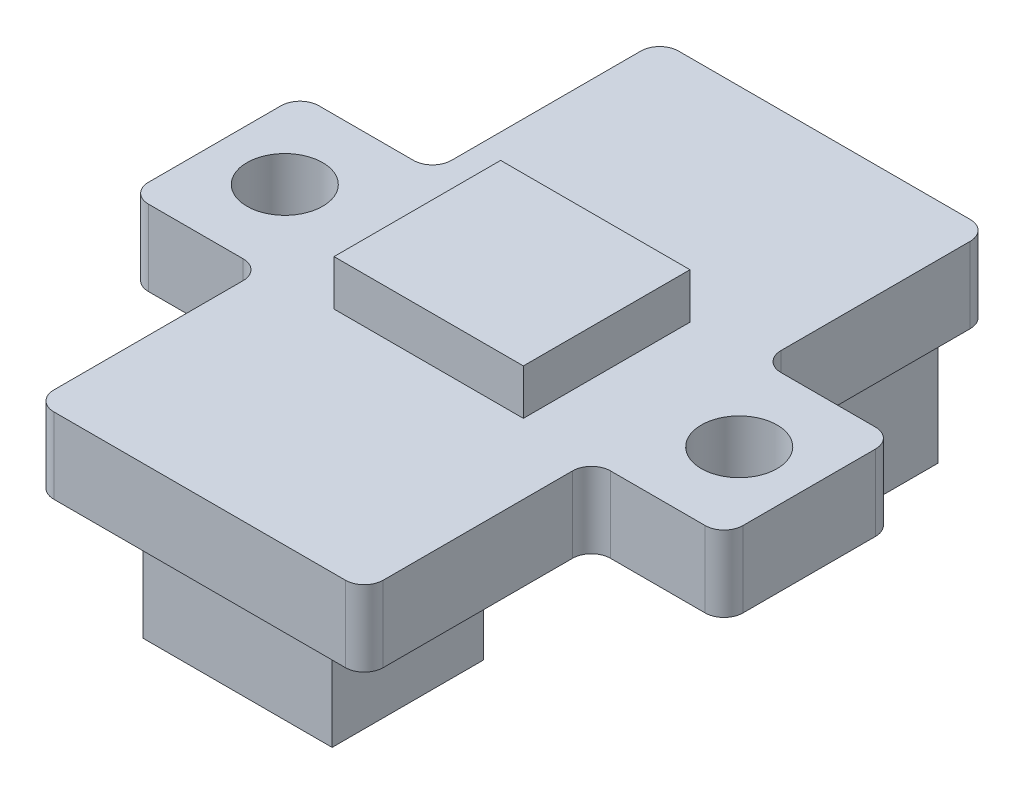
SolidWorks part; units mm, degrees
ref_plane "Front Plane" through (0, 0, 0) normal (0, 0, 1) x (1, 0, 0)
ref_plane "Top Plane" through (0, 0, 0) normal (0, 1, 0) x (1, 0, 0)
ref_plane "Right Plane" through (0, 0, 0) normal (1, 0, 0) x (0, 0, -1)
sketch "Sketch1" plane through (0, 0, 0) normal (0, 1, 0) x (1, 0, 0)
  line L0 (0, 0) -> (0, 8.25) construction
  line L1 (-7.85, 8.25) -> (7.85, 8.25) construction
  line L2 (-7.85, 8.25) -> (-7.85, -8.25) construction
  line L3 (-7.85, -8.25) -> (7.85, -8.25) construction
  line L4 (7.85, 8.25) -> (7.85, -8.25) construction
  line L5 (-7.85, 8.25) -> (7.85, -8.25) construction
  line L6 (-7.85, -8.25) -> (7.85, 8.25) construction
  line L7 (-4.35, 8.25) -> (4.35, 8.25)
  line L8 (-4.35, 8.25) -> (-4.35, -8.25)
  line L9 (-4.35, -8.25) -> (4.35, -8.25)
  line L10 (4.35, 8.25) -> (4.35, -8.25)
  line L11 (0, 0) -> (7.85, 0) construction
  line L13 (-7.85, 2.25) -> (7.85, 2.25)
  line L14 (-7.85, 2.25) -> (-7.85, -2.25)
  line L15 (-7.85, -2.25) -> (7.85, -2.25)
  line L16 (7.85, 2.25) -> (7.85, -2.25)
  circle A0 centre (6, 0) radius 1
  circle A1 centre (-6, 0) radius 1
  point P0 (0, 0)
  dimension "D5" = 2
  dimension "D1" = 15.7
  dimension "D2" = 16.5
  dimension "D3" = 8.7
  dimension "D4" = 12
  dimension "D6" = 4.5
extrude "Boss-Extrude1" add sketch "Sketch1" along normal blind 2 contours L8 L13 L10 L7 | L8 L15 L10 L13 | L14 L15 L8 L13 A1 | L16 L13 L10 L15 A0 | L15 L8 L9 L10
fillet "Fillet1" radius 0.5 12 edges at (-7.85, 1, -2.25) (-4.35, 1, -2.25) (-4.35, 1, -8.25) (4.35, 1, -8.25) (4.35, 1, -2.25) (7.85, 1, -2.25) (7.85, 1, 2.25) (4.35, 1, 2.25) (4.35, 1, 8.25) (-4.35, 1, 8.25) (-7.85, 1, 2.25) (-4.35, 1, 2.25)
sketch "Sketch2" plane through (0, 0, 0) normal (0, -1, 0) x (1, 0, 0)
  line L0 (0, 8.25) -> (0, -8.25) construction
  line L1 (-2.5, 7.25) -> (2.5, 7.25)
  line L2 (-2.5, 7.25) -> (-2.5, 3.25)
  line L3 (-2.5, 3.25) -> (2.5, 3.25)
  line L4 (2.5, 7.25) -> (2.5, 3.25)
  line L5 (-3.85, -8.25) -> (3.85, -8.25) construction
  line L6 (-4, -2.75) -> (4, -2.75)
  line L7 (-4, -2.75) -> (-4, -7.25)
  line L8 (-4, -7.25) -> (4, -7.25)
  line L9 (4, -2.75) -> (4, -7.25)
  line L12 (-7.35, -2.25) -> (-4.85, -2.25)
  line L13 (-3.85, -8.25) -> (3.85, -8.25)
  line L14 (-7.35, -2.25) -> (-4.85, -2.25)
  line L15 (-4.35, -2.75) -> (-4.35, -7.75)
  line L16 (7.85, -1.75) -> (7.85, 1.75)
  line L17 (-4.35, -2.75) -> (-4.35, -7.75)
  line L18 (4.35, -7.75) -> (4.35, -2.75)
  line L19 (3.85, 8.25) -> (-3.85, 8.25)
  line L20 (4.35, -7.75) -> (4.35, -2.75)
  line L21 (4.85, -2.25) -> (7.35, -2.25)
  line L22 (-7.85, 1.75) -> (-7.85, -1.75)
  line L23 (4.85, -2.25) -> (7.35, -2.25)
  line L25 (-3.85, -8.25) -> (3.85, -8.25) construction
  line L28 (7.85, -1.75) -> (7.85, 1.75) construction
  line L31 (3.85, 8.25) -> (-3.85, 8.25) construction
  line L34 (-7.85, 1.75) -> (-7.85, -1.75) construction
  line L46 (7.35, 2.25) -> (4.85, 2.25)
  line L47 (7.35, 2.25) -> (4.85, 2.25)
  line L48 (4.35, 2.75) -> (4.35, 7.75)
  line L49 (4.35, 2.75) -> (4.35, 7.75)
  line L50 (-4.35, 7.75) -> (-4.35, 2.75)
  line L51 (-4.35, 7.75) -> (-4.35, 2.75)
  line L52 (-4.85, 2.25) -> (-7.35, 2.25)
  line L53 (-4.85, 2.25) -> (-7.35, 2.25)
  arc A12 (-7.85, -1.75) -> (-7.35, -2.25) centre (-7.35, -1.75) ccw
  arc A13 (-7.85, -1.75) -> (-7.35, -2.25) centre (-7.35, -1.75) ccw
  arc A14 (-4.35, -2.75) -> (-4.85, -2.25) centre (-4.85, -2.75) ccw
  arc A15 (-4.35, -2.75) -> (-4.85, -2.25) centre (-4.85, -2.75) ccw
  arc A16 (-4.35, -7.75) -> (-3.85, -8.25) centre (-3.85, -7.75) ccw
  arc A17 (-4.35, -7.75) -> (-3.85, -8.25) centre (-3.85, -7.75) ccw
  arc A18 (3.85, -8.25) -> (4.35, -7.75) centre (3.85, -7.75) ccw
  arc A19 (3.85, -8.25) -> (4.35, -7.75) centre (3.85, -7.75) ccw
  arc A20 (4.85, -2.25) -> (4.35, -2.75) centre (4.85, -2.75) ccw
  arc A21 (4.85, -2.25) -> (4.35, -2.75) centre (4.85, -2.75) ccw
  arc A22 (7.35, -2.25) -> (7.85, -1.75) centre (7.35, -1.75) ccw
  arc A23 (7.35, -2.25) -> (7.85, -1.75) centre (7.35, -1.75) ccw
  arc A24 (7.85, 1.75) -> (7.35, 2.25) centre (7.35, 1.75) ccw
  arc A25 (7.85, 1.75) -> (7.35, 2.25) centre (7.35, 1.75) ccw
  arc A26 (4.35, 2.75) -> (4.85, 2.25) centre (4.85, 2.75) ccw
  arc A27 (4.35, 2.75) -> (4.85, 2.25) centre (4.85, 2.75) ccw
  arc A28 (4.35, 7.75) -> (3.85, 8.25) centre (3.85, 7.75) ccw
  arc A29 (4.35, 7.75) -> (3.85, 8.25) centre (3.85, 7.75) ccw
  arc A30 (-3.85, 8.25) -> (-4.35, 7.75) centre (-3.85, 7.75) ccw
  arc A31 (-3.85, 8.25) -> (-4.35, 7.75) centre (-3.85, 7.75) ccw
  arc A32 (-4.85, 2.25) -> (-4.35, 2.75) centre (-4.85, 2.75) ccw
  arc A33 (-4.85, 2.25) -> (-4.35, 2.75) centre (-4.85, 2.75) ccw
  arc A34 (-7.35, 2.25) -> (-7.85, 1.75) centre (-7.35, 1.75) ccw
  arc A35 (-7.35, 2.25) -> (-7.85, 1.75) centre (-7.35, 1.75) ccw
  dimension "D2" = 1
  dimension "D3" = 4
  dimension "D4" = 5
  dimension "D5" = 8
  dimension "D6" = 1
  dimension "D7" = 4.5
  dimension "D1" = 0
extrude "Boss-Extrude2" add sketch "Sketch2" along normal blind 3 contours L9 L6 L7 L8 | L2 L1 L4 L3
sketch "Sketch3" plane through (0, 2, 0) normal (0, 1, 0) x (1, 0, 0)
  line L1 (-2.5, 2.2) -> (2.5, 2.2)
  line L2 (-2.5, 2.2) -> (-2.5, -2.2)
  line L3 (-2.5, -2.2) -> (2.5, -2.2)
  line L4 (2.5, 2.2) -> (2.5, -2.2)
  line L5 (-2.5, 2.2) -> (2.5, -2.2) construction
  line L6 (-2.5, -2.2) -> (2.5, 2.2) construction
  point P0 (0, 0)
  dimension "D1" = 4.4
  dimension "D2" = 5
extrude "Boss-Extrude3" add sketch "Sketch3" along normal blind 1.2
